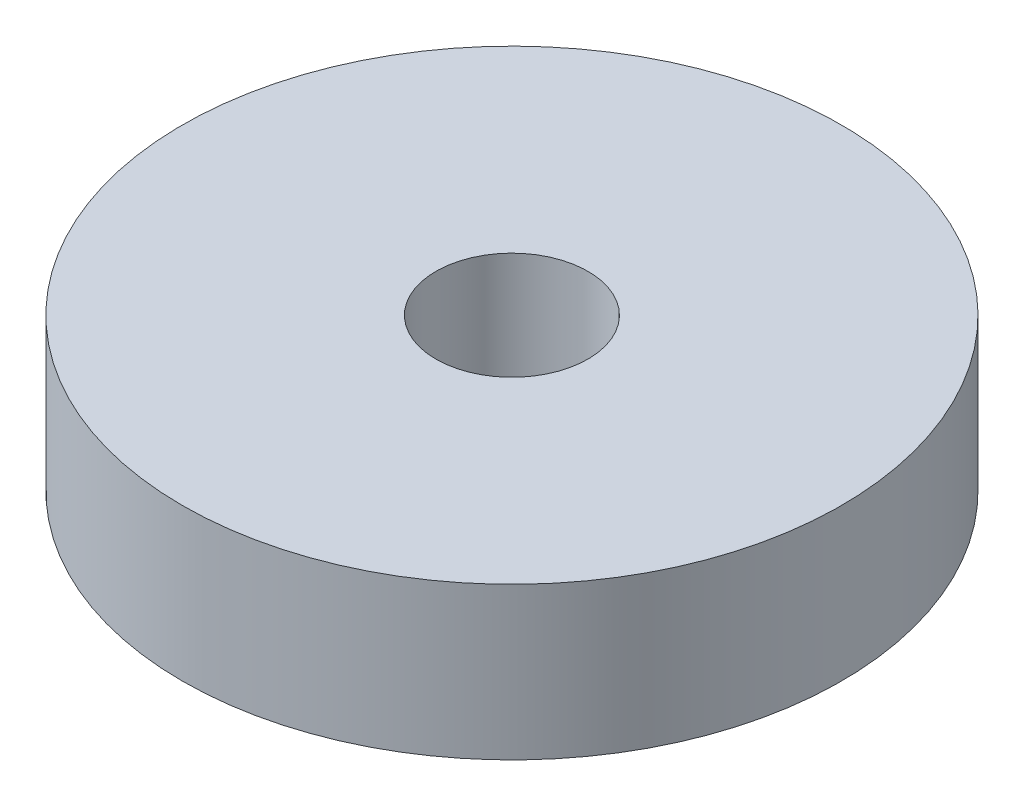
SolidWorks part; units mm, degrees
ref_plane "Front Plane" through (0, 0, 0) normal (0, 0, 1) x (1, 0, 0)
ref_plane "Top Plane" through (0, 0, 0) normal (0, 1, 0) x (1, 0, 0)
ref_plane "Right Plane" through (0, 0, 0) normal (1, 0, 0) x (0, 0, -1)
sketch "Sketch1" plane through (0, 0, 0) normal (0, 1, 0) x (1, 0, 0)
  circle A0 centre (0, 0) radius 6.5
  circle A1 centre (0, 0) radius 1.5
extrude "Boss-Extrude1" add sketch "Sketch1" along normal blind 3
